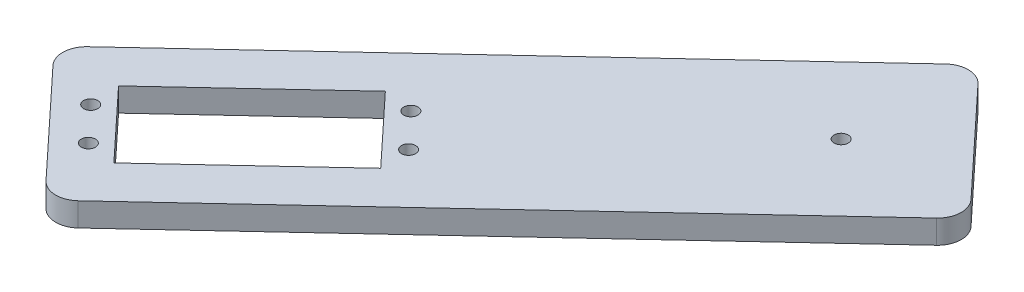
SolidWorks part; units mm, degrees
ref_plane "前视基准面" through (0, 0, 0) normal (0, 0, 1) x (1, 0, 0)
ref_plane "上视基准面" through (0, 0, 0) normal (0, 1, 0) x (1, 0, 0)
ref_plane "右视基准面" through (0, 0, 0) normal (1, 0, 0) x (0, 0, -1)
sketch "草图1" plane through (0, 0, 0) normal (0, 1, 0) x (1, 0, 0)
  line L16 (-90.8957, -126.1625) -> (-61.6415, -98.8825)
  line L17 (-61.6415, -98.8825) -> (-75.2815, -84.2554)
  line L18 (-75.2815, -84.2554) -> (-104.5356, -111.5354)
  line L19 (-90.8957, -126.1625) -> (-104.5356, -111.5354)
  line L26 (-20.911, -19.8809) -> (-115.0124, -107.6318)
  line L27 (6.3689, -49.135) -> (-87.7325, -136.886)
  line L28 (-94.7992, -136.6392) -> (-115.2592, -114.6986)
  line L33 (6.6157, -42.0683) -> (-13.8443, -20.1277)
  circle A15 centre (-97.2311, -125.2337) radius 1.5
  circle A16 centre (-104.0511, -117.9201) radius 1.5
  circle A17 centre (-62.1261, -92.4978) radius 1.5
  circle A18 centre (-68.9461, -85.1842) radius 1.5
  arc A27 (-94.7992, -136.6392) -> (-87.7325, -136.886) centre (-91.1424, -133.2292) ccw
  arc A28 (-115.0124, -107.6318) -> (-115.2592, -114.6986) centre (-111.6024, -111.2886) ccw
  circle A33 centre (-18.2414, -44.7379) radius 1.5
  arc A34 (-20.911, -19.8809) -> (-13.8443, -20.1277) centre (-17.501, -23.5376) cw
  arc A35 (6.6157, -42.0683) -> (6.3689, -49.135) centre (2.9589, -45.4783) cw
extrude "凸台-拉伸1" add sketch "草图1" along normal blind 5
